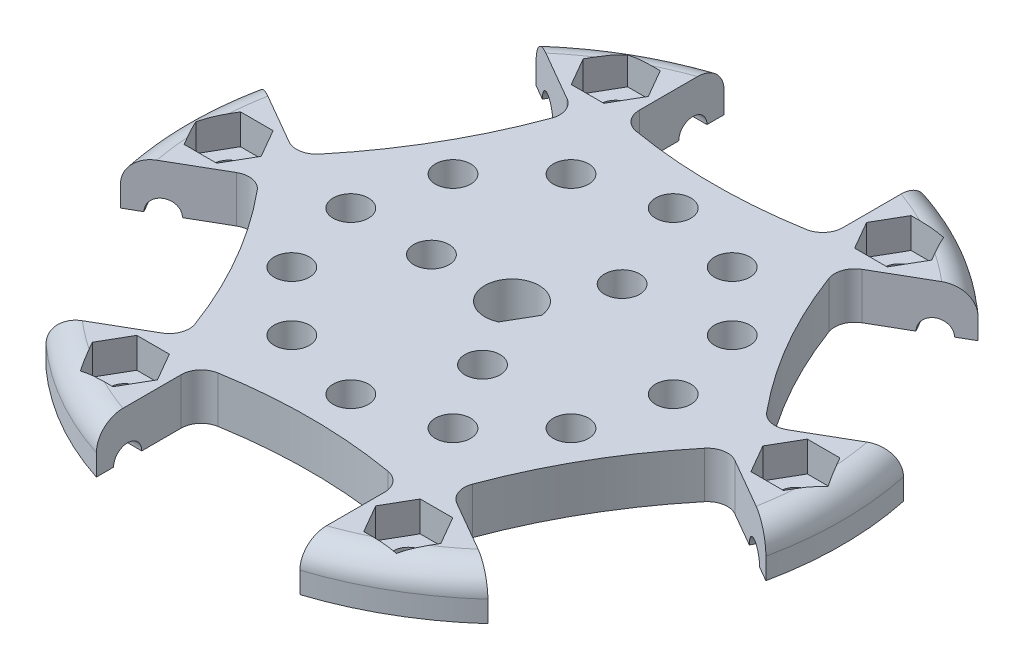
SolidWorks part; units mm, degrees
ref_plane "Plano frontal" through (0, 0, 0) normal (0, 0, 1) x (1, 0, 0)
ref_plane "Plano superior" through (0, 0, 0) normal (0, 1, 0) x (1, 0, 0)
ref_plane "Plano direito" through (0, 0, 0) normal (1, 0, 0) x (0, 0, -1)
sketch "Esboço1" plane through (0, 0, 0) normal (0, 0, 1) x (1, 0, 0)
  line L1 (-32.75, 2.1) -> (-32.75, 0)
  line L2 (-30.25, 4.6) -> (-6.07, 4.6)
  line L15 (-6.07, 4.6) -> (0, 4.6)
  line L17 (0, 0) -> (0, 4.6)
  line L18 (-32.75, 0) -> (0, 0)
  arc A3 (-30.25, 4.6) -> (-32.75, 2.1) centre (-30.25, 2.1) ccw
revolve "Revolução3" add sketch "Esboço1" angle 360 about L17
sketch "Esboço3" plane through (0, 0, 0) normal (0, -1, 0) x (1, 0, 0)
  line L2 (-10.1, 71.55) -> (10.1, 71.55)
  line L3 (-10.1, 71.55) -> (-10.1, 22.7384)
  line L4 (10.1, 71.55) -> (10.1, 22.7384)
  line L5 (10.1, -71.55) -> (-10.1, -71.55)
  line L6 (10.1, -71.55) -> (10.1, -22.7384)
  line L7 (-10.1, -71.55) -> (-10.1, -22.7384)
  line L10 (56.9141, 44.5219) -> (67.0141, 27.0281)
  line L11 (56.9141, 44.5219) -> (14.642, 20.116)
  line L12 (67.0141, 27.0281) -> (24.742, 2.6223)
  line L13 (-56.9141, -44.5219) -> (-67.0141, -27.0281)
  line L14 (-56.9141, -44.5219) -> (-14.642, -20.116)
  line L15 (-67.0141, -27.0281) -> (-24.742, -2.6223)
  line L18 (-67.0141, 27.0281) -> (-56.9141, 44.5219)
  line L19 (-67.0141, 27.0281) -> (-24.742, 2.6223)
  line L20 (-56.9141, 44.5219) -> (-14.642, 20.116)
  line L21 (67.0141, -27.0281) -> (56.9141, -44.5219)
  line L22 (67.0141, -27.0281) -> (24.742, -2.6223)
  line L23 (56.9141, -44.5219) -> (14.642, -20.116)
  arc A1 (-8.4375, 20.7671) -> (8.4375, 20.7671) centre (0, 70.05) ccw
  arc A2 (8.4375, 20.7671) -> (10.1, 22.7384) centre (8.1, 22.7384) ccw
  arc A3 (-8.4375, 20.7671) -> (-10.1, 22.7384) centre (-8.1, 22.7384) cw
  arc A4 (8.4375, -20.7671) -> (-8.4375, -20.7671) centre (0, -70.05) ccw
  arc A5 (-8.4375, -20.7671) -> (-10.1, -22.7384) centre (-8.1, -22.7384) ccw
  arc A6 (8.4375, -20.7671) -> (10.1, -22.7384) centre (8.1, -22.7384) cw
  arc A7 (13.766, 17.6906) -> (22.2035, 3.0764) centre (60.6651, 35.025) ccw
  arc A8 (22.2035, 3.0764) -> (24.742, 2.6223) centre (23.742, 4.3544) ccw
  arc A9 (13.766, 17.6906) -> (14.642, 20.116) centre (15.642, 18.384) cw
  arc A10 (-13.766, -17.6906) -> (-22.2035, -3.0764) centre (-60.6651, -35.025) ccw
  arc A11 (-22.2035, -3.0764) -> (-24.742, -2.6223) centre (-23.742, -4.3544) ccw
  arc A12 (-13.766, -17.6906) -> (-14.642, -20.116) centre (-15.642, -18.384) cw
  arc A13 (-22.2035, 3.0764) -> (-13.766, 17.6906) centre (-60.6651, 35.025) ccw
  arc A14 (-13.766, 17.6906) -> (-14.642, 20.116) centre (-15.642, 18.384) ccw
  arc A15 (-22.2035, 3.0764) -> (-24.742, 2.6223) centre (-23.742, 4.3544) cw
  arc A16 (22.2035, -3.0764) -> (13.766, -17.6906) centre (60.6651, -35.025) ccw
  arc A17 (13.766, -17.6906) -> (14.642, -20.116) centre (15.642, -18.384) ccw
  arc A18 (22.2035, -3.0764) -> (24.742, -2.6223) centre (23.742, -4.3544) cw
extrude "Corte-extrusão2" cut sketch "Esboço3" against normal blind 10
sketch "Esboço5" plane through (0, 0, 0) normal (0, -1, 0) x (1, 0, 0)
  line L0 (-12.6, 26.65) -> (12.6, 26.65)
  line L1 (-12.6, 28.05) -> (12.6, 28.05)
  line L10 (-12.6, 28.05) -> (-12.6, 26.65)
  line L13 (12.6, 28.05) -> (12.6, 26.65)
revolve "Corte-Revolução3" cut sketch "Esboço5" angle 360 about L1
sketch "Esboço6" plane through (0, 0, 0) normal (0, -1, 0) x (1, 0, 0)
  line L21 (-29.3796, 2.4131) -> (-16.7796, 24.2369)
  line L22 (-30.592, 3.1131) -> (-17.992, 24.9369)
  line L23 (-30.592, 3.1131) -> (-29.3796, 2.4131)
  line L24 (-17.992, 24.9369) -> (-16.7796, 24.2369)
revolve "Corte-Revolução4" cut sketch "Esboço6" angle 360 about L22
sketch "Esboço7" plane through (0, 0, 0) normal (0, -1, 0) x (1, 0, 0)
  line L9 (-16.7796, -24.2369) -> (-29.3796, -2.4131)
  line L10 (-17.992, -24.9369) -> (-30.592, -3.1131)
  line L11 (-17.992, -24.9369) -> (-16.7796, -24.2369)
  line L12 (-30.592, -3.1131) -> (-29.3796, -2.4131)
revolve "Corte-Revolução5" cut sketch "Esboço7" angle 360 about L10
sketch "Esboço8" plane through (0, 0, 0) normal (0, -1, 0) x (1, 0, 0)
  line L13 (16.7796, 24.2369) -> (29.3796, 2.4131)
  line L14 (17.992, 24.9369) -> (30.592, 3.1131)
  line L15 (17.992, 24.9369) -> (16.7796, 24.2369)
  line L16 (30.592, 3.1131) -> (29.3796, 2.4131)
revolve "Corte-Revolução6" cut sketch "Esboço8" angle 360 about L14
sketch "Esboço10" plane through (0, 0, 0) normal (0, -1, 0) x (1, 0, 0)
  line L1 (12.6, -26.65) -> (-12.6, -26.65)
  line L2 (12.6, -28.05) -> (-12.6, -28.05)
  line L3 (12.6, -28.05) -> (12.6, -26.65)
  line L4 (-12.6, -28.05) -> (-12.6, -26.65)
revolve "Corte-Revolução7" cut sketch "Esboço10" angle 360 about L2
sketch "Esboço11" plane through (0, 0, 0) normal (0, -1, 0) x (1, 0, 0)
  line L5 (29.3796, -2.4131) -> (16.7796, -24.2369)
  line L6 (30.592, -3.1131) -> (17.992, -24.9369)
  line L7 (30.592, -3.1131) -> (29.3796, -2.4131)
  line L8 (17.992, -24.9369) -> (16.7796, -24.2369)
revolve "Corte-Revolução8" cut sketch "Esboço11" angle 360 about L6
sketch "Esboço12" plane through (0, 0, 0) normal (0, -1, 0) x (1, 0, 0)
  circle A1 centre (0, 16) radius 1.75
  circle A2 centre (-8, 13.8564) radius 1.75
  circle A3 centre (-13.8564, 8) radius 1.75
  circle A4 centre (-16, 0) radius 1.75
  circle A5 centre (-13.8564, -8) radius 1.75
  circle A6 centre (-8, -13.8564) radius 1.75
  circle A7 centre (0, -16) radius 1.75
  circle A8 centre (8, -13.8564) radius 1.75
  circle A9 centre (13.8564, -8) radius 1.75
  circle A10 centre (16, 0) radius 1.75
  circle A11 centre (13.8564, 8) radius 1.75
  circle A12 centre (8, 13.8564) radius 1.75
  circle A13 centre (28.1296, 0) radius 1.3
  circle A14 centre (14.0648, 24.3609) radius 1.3
  circle A15 centre (-14.0648, 24.3609) radius 1.3
  circle A16 centre (-28.1296, 0) radius 1.3
  circle A18 centre (14.0648, -24.3609) radius 1.3
  circle A19 centre (-14.0648, -24.3609) radius 1.3
sketch "Esboço13" plane through (0, 0, 0) normal (0, -1, 0) x (1, 0, 0)
  line L2 (2.5851, -0.2776) -> (1.0522, 2.3776)
  arc A0 (1.0522, 2.3776) -> (2.5851, -0.2776) centre (0, 0) ccw
extrude "Corte-extrusão9" cut sketch "Esboço12" against normal through all
sketch "Esboço17" plane through (0, 0, 0) normal (0, -1, 0) x (1, 0, 0)
  circle A0 centre (4, 6.9282) radius 1.75
  circle A1 centre (-8, 0) radius 1.75
  circle A2 centre (4, -6.9282) radius 1.75
extrude "Corte-extrusão10" cut sketch "Esboço17" against normal through all
extrude "Corte-extrusão11" cut sketch "Esboço13" against normal through all
sketch "Esboço18" plane through (0, 4.6, 0) normal (0, 1, 0) x (1, 0, 0)
  line L1 (-31.0163, 0) -> (-29.573, -2.5)
  line L2 (-29.573, -2.5) -> (-26.6862, -2.5)
  line L3 (-26.6862, -2.5) -> (-25.2428, 0)
  line L4 (-25.2428, 0) -> (-26.6862, 2.5)
  line L5 (-26.6862, 2.5) -> (-29.573, 2.5)
  line L6 (-29.573, 2.5) -> (-31.0163, 0)
  line L8 (-15.5082, 26.8609) -> (-16.9515, 24.3609)
  line L9 (-16.9515, 24.3609) -> (-15.5082, 21.8609)
  line L10 (-15.5082, 21.8609) -> (-12.6214, 21.8609)
  line L11 (-12.6214, 21.8609) -> (-11.178, 24.3609)
  line L12 (-11.178, 24.3609) -> (-12.6214, 26.8609)
  line L13 (-12.6214, 26.8609) -> (-15.5082, 26.8609)
  line L15 (15.5082, 26.8609) -> (12.6214, 26.8609)
  line L16 (12.6214, 26.8609) -> (11.178, 24.3609)
  line L17 (11.178, 24.3609) -> (12.6214, 21.8609)
  line L18 (12.6214, 21.8609) -> (15.5082, 21.8609)
  line L19 (15.5082, 21.8609) -> (16.9515, 24.3609)
  line L20 (16.9515, 24.3609) -> (15.5082, 26.8609)
  line L22 (31.0163, 0) -> (29.573, 2.5)
  line L23 (29.573, 2.5) -> (26.6862, 2.5)
  line L24 (26.6862, 2.5) -> (25.2428, 0)
  line L25 (25.2428, 0) -> (26.6862, -2.5)
  line L26 (26.6862, -2.5) -> (29.573, -2.5)
  line L27 (29.573, -2.5) -> (31.0163, 0)
  line L29 (15.5082, -26.8609) -> (16.9515, -24.3609)
  line L30 (16.9515, -24.3609) -> (15.5082, -21.8609)
  line L31 (15.5082, -21.8609) -> (12.6214, -21.8609)
  line L32 (12.6214, -21.8609) -> (11.178, -24.3609)
  line L33 (11.178, -24.3609) -> (12.6214, -26.8609)
  line L34 (12.6214, -26.8609) -> (15.5082, -26.8609)
  line L36 (-15.5082, -26.8609) -> (-12.6214, -26.8609)
  line L37 (-12.6214, -26.8609) -> (-11.178, -24.3609)
  line L38 (-11.178, -24.3609) -> (-12.6214, -21.8609)
  line L39 (-12.6214, -21.8609) -> (-15.5082, -21.8609)
  line L40 (-15.5082, -21.8609) -> (-16.9515, -24.3609)
  line L41 (-16.9515, -24.3609) -> (-15.5082, -26.8609)
  circle A0 centre (-28.1296, 0) radius 2.5 construction
  circle A1 centre (-14.0648, 24.3609) radius 2.5 construction
  circle A2 centre (14.0648, 24.3609) radius 2.5 construction
  circle A3 centre (28.1296, 0) radius 2.5 construction
  circle A4 centre (14.0648, -24.3609) radius 2.5 construction
  circle A5 centre (-14.0648, -24.3609) radius 2.5 construction
extrude "Corte-extrusão12" cut sketch "Esboço18" against normal blind 3
sketch "Esboço19" plane through (0, 4.6, 0) normal (0, 1, 0) x (1, 0, 0)
  circle A0 centre (-14.0648, 24.3609) radius 1.5
  circle A1 centre (14.0648, 24.3609) radius 1.5
  circle A2 centre (14.0648, -24.3609) radius 1.5
  circle A3 centre (-14.0648, -24.3609) radius 1.5
  circle A4 centre (-28.1296, 0) radius 1.5
  circle A5 centre (28.1296, 0) radius 1.5
extrude "Corte-extrusão13" cut sketch "Esboço19" against normal through all
sketch "Esboço20" plane through (0, 4.6, 0) normal (0, 1, 0) x (1, 0, 0)
  line L0 (26.513, -2.8) -> (29.7462, -2.8)
  line L1 (-29.7462, 2.8) -> (-31.3627, 0)
  line L2 (-31.3627, 0) -> (-29.7462, -2.8)
  line L3 (-29.7462, -2.8) -> (-26.513, -2.8)
  line L4 (-26.513, -2.8) -> (-24.8964, 0)
  line L5 (-24.8964, 0) -> (-26.513, 2.8)
  line L6 (-26.513, 2.8) -> (-29.7462, 2.8)
  line L7 (29.7462, -2.8) -> (31.3627, 0)
  line L8 (29.7462, 2.8) -> (26.513, 2.8)
  line L9 (24.8964, 0) -> (26.513, -2.8)
  line L10 (26.513, 2.8) -> (24.8964, 0)
  line L11 (31.3627, 0) -> (29.7462, 2.8)
  line L12 (15.6814, 27.1609) -> (12.4482, 27.1609)
  line L13 (10.8316, 24.3609) -> (12.4482, 21.5609)
  line L14 (17.298, 24.3609) -> (15.6814, 27.1609)
  line L15 (12.4482, 27.1609) -> (10.8316, 24.3609)
  line L16 (15.6814, 21.5609) -> (17.298, 24.3609)
  line L17 (12.4482, 21.5609) -> (15.6814, 21.5609)
  line L18 (-10.8316, 24.3609) -> (-12.4482, 27.1609)
  line L19 (-12.4482, 21.5609) -> (-10.8316, 24.3609)
  line L20 (-12.4482, 27.1609) -> (-15.6814, 27.1609)
  line L21 (-17.298, 24.3609) -> (-15.6814, 21.5609)
  line L22 (-15.6814, 27.1609) -> (-17.298, 24.3609)
  line L23 (-15.6814, 21.5609) -> (-12.4482, 21.5609)
  line L24 (-15.6814, -27.1609) -> (-12.4482, -27.1609)
  line L25 (-12.4482, -27.1609) -> (-10.8316, -24.3609)
  line L26 (-15.6814, -21.5609) -> (-17.298, -24.3609)
  line L27 (17.298, -24.3609) -> (15.6814, -21.5609)
  line L28 (-12.4482, -21.5609) -> (-15.6814, -21.5609)
  line L29 (15.6814, -27.1609) -> (17.298, -24.3609)
  line L30 (12.4482, -21.5609) -> (10.8316, -24.3609)
  line L31 (10.8316, -24.3609) -> (12.4482, -27.1609)
  line L32 (-17.298, -24.3609) -> (-15.6814, -27.1609)
  line L33 (15.6814, -21.5609) -> (12.4482, -21.5609)
  line L34 (12.4482, -27.1609) -> (15.6814, -27.1609)
  line L35 (-10.8316, -24.3609) -> (-12.4482, -21.5609)
  circle A0 centre (-28.1296, 0) radius 2.8 construction
  circle A1 centre (28.1296, 0) radius 2.8 construction
  circle A2 centre (14.0648, 24.3609) radius 2.8 construction
  circle A3 centre (-14.0648, 24.3609) radius 2.8 construction
  circle A4 centre (14.0648, -24.3609) radius 2.8 construction
  circle A5 centre (-14.0648, -24.3609) radius 2.8 construction
extrude "Corte-extrusão14" cut sketch "Esboço20" against normal blind 3
sketch "Esboço21" plane through (0, 4.6, 0) normal (0, 1, 0) x (1, 0, 0)
  line L2 (1.1226, -2.4555) -> (2.6879, 0.2555)
  arc A0 (2.6879, 0.2555) -> (1.1226, -2.4555) centre (0, 0) ccw
extrude "Corte-extrusão15" cut sketch "Esboço21" against normal through all
